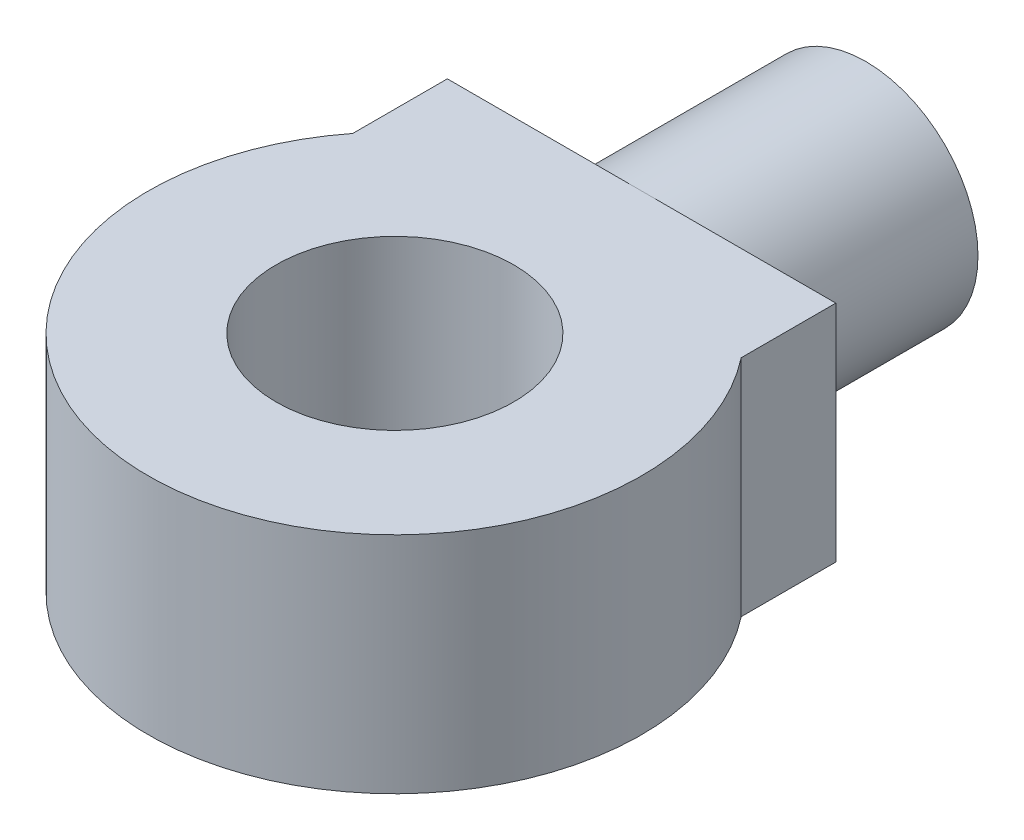
SolidWorks part; units mm, degrees
ref_plane "Front Plane" through (0, 0, 0) normal (0, 0, 1) x (1, 0, 0)
ref_plane "Top Plane" through (0, 0, 0) normal (0, 1, 0) x (1, 0, 0)
ref_plane "Right Plane" through (0, 0, 0) normal (1, 0, 0) x (0, 0, -1)
sketch "Sketch1" plane through (0, 0, 2.5962) normal (0, 0, 1) x (1, 0, 0)
  circle A0 centre (21.0048, 129.3152) radius 2.5
  dimension "D1" = 5
extrude "Boss-Extrude1" add sketch "Sketch1" against normal blind 5
sketch "Sketch2" plane through (0, 0, 2.5962) normal (0, 0, 1) x (1, 0, 0)
  line L1 (16.6747, 131.8152) -> (25.3349, 131.8152)
  line L2 (16.6747, 131.8152) -> (16.6747, 126.8152)
  line L3 (16.6747, 126.8152) -> (25.3349, 126.8152)
  line L4 (25.3349, 131.8152) -> (25.3349, 126.8152)
  line L5 (16.6747, 131.8152) -> (25.3349, 126.8152) construction
  line L6 (16.6747, 126.8152) -> (25.3349, 131.8152) construction
  circle A0 centre (21.0048, 129.3152) radius 2.5 construction
  circle A2 centre (21.0048, 129.3152) radius 5 construction
  point P4 (21.0048, 129.3152)
  dimension "D1" = 5
extrude "Boss-Extrude2" add sketch "Sketch2" along normal blind 5
sketch "Sketch3" plane through (0, 131.8152, 0) normal (0, 1, 0) x (1, 0, 0)
  line L0 (21.0048, -8.0962) -> (21.0048, -7.5962) construction
  line L1 (25.3349, -7.5962) -> (16.6747, -7.5962) construction
  line L5 (25.3349, -2.5962) -> (21.0048, -2.5962) construction
  circle A0 centre (21.0048, -8.0962) radius 5.5
  dimension "D1" = 11
extrude "Boss-Extrude3" add sketch "Sketch3" against normal up to surface (5 mm away) up to face at (21.0048, 126.8152, 4.5962)
sketch "Sketch4" plane through (0, 131.8152, 0) normal (0, 1, 0) x (1, 0, 0)
  circle A0 centre (21.0048, -8.0962) radius 2.65
  dimension "D1" = 5.3
extrude "Cut-Extrude1" cut sketch "Sketch4" against normal through all
move or copy body "Body-Move/Copy1" bodies to move or copy 104 copy no translate (-21, -129.32, -8.1)
